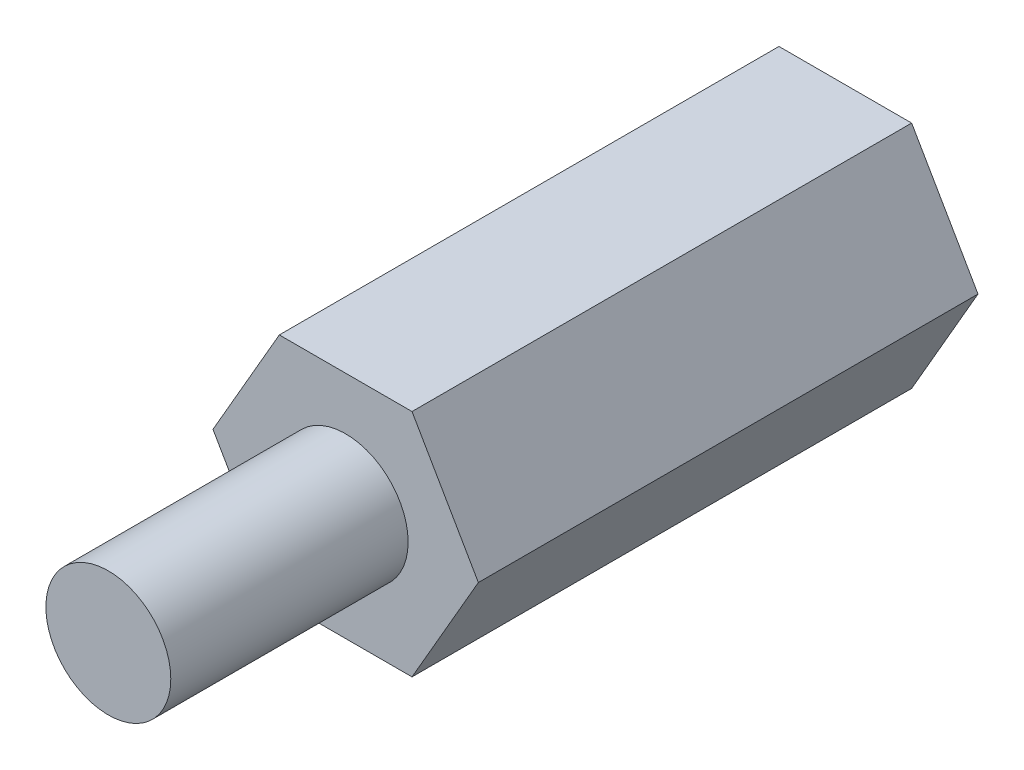
SolidWorks part; units mm, degrees
ref_plane "Ebene vorne" through (0, 0, 0) normal (0, 0, 1) x (1, 0, 0)
ref_plane "Ebene oben" through (0, 0, 0) normal (0, 1, 0) x (1, 0, 0)
ref_plane "Ebene rechts" through (0, 0, 0) normal (1, 0, 0) x (0, 0, -1)
sketch "Skizze1" plane through (0, 0, 0) normal (0, 0, 1) x (1, 0, 0)
  line L1 (2.6558, 0) -> (1.3279, 2.3)
  line L2 (1.3279, 2.3) -> (-1.3279, 2.3)
  line L3 (-1.3279, 2.3) -> (-2.6558, 0)
  line L4 (-2.6558, 0) -> (-1.3279, -2.3)
  line L5 (-1.3279, -2.3) -> (1.3279, -2.3)
  line L6 (1.3279, -2.3) -> (2.6558, 0)
  circle A0 centre (0, 0) radius 2.3 construction
  dimension "D1" = 4.6
extrude "Body" add sketch "Skizze1" along normal blind 10
sketch "Skizze2" plane through (0, 0, 10) normal (0, 0, 1) x (1, 0, 0)
  circle A0 centre (0, 0) radius 1.25
  dimension "D1" = 2.5
extrude "Thread" add sketch "Skizze2" along normal blind 4.75
sketch "Skizze3" plane through (0, 0, 0) normal (0, 0, -1) x (-1, 0, 0)
  circle A0 centre (0, 0) radius 1.25
  dimension "D1" = 2.5
extrude "Schnitt-Linear austragen1" cut sketch "Skizze3" against normal blind 6.4 contours A0
